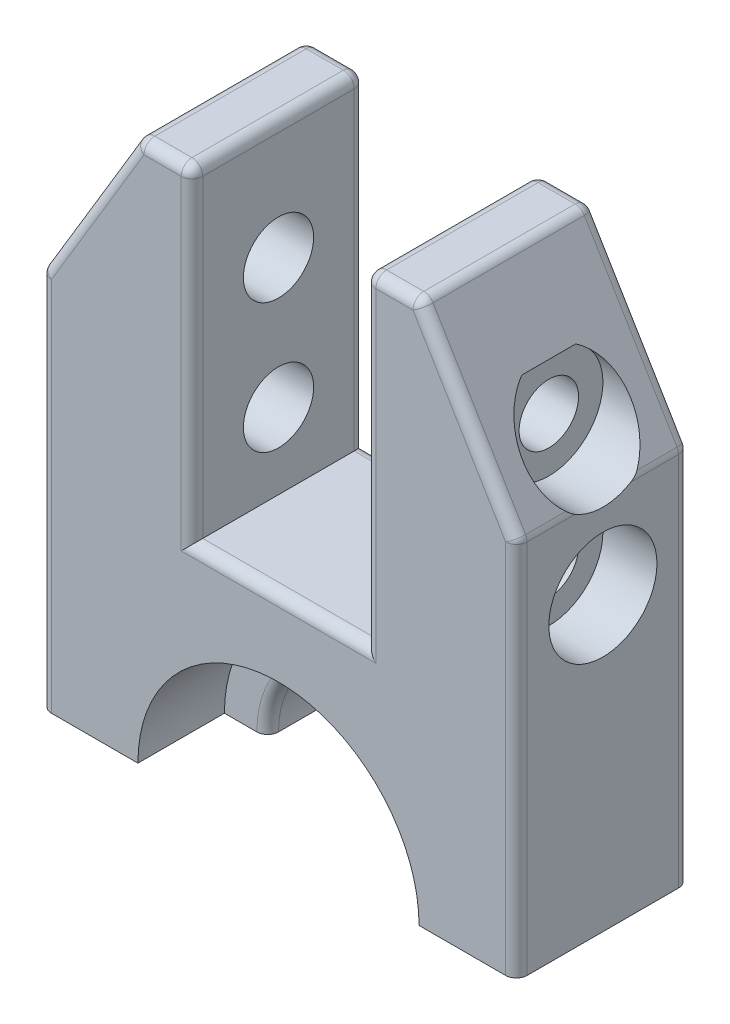
SolidWorks part; units mm, degrees
ref_plane "Płaszczyzna przednia" through (0, 0, 0) normal (0, 0, 1) x (1, 0, 0)
ref_plane "Płaszczyzna górna" through (0, 0, 0) normal (0, 1, 0) x (1, 0, 0)
ref_plane "Płaszczyzna prawa" through (0, 0, 0) normal (1, 0, 0) x (0, 0, -1)
sketch "Szkic1" plane through (0, 0, 0) normal (0, 0, 1) x (1, 0, 0)
  line L0 (0, 0) -> (8, 0)
  line L1 (22, 15) -> (22, -20)
  line L2 (22, -20) -> (0, -20)
  line L3 (0, -20) -> (0, 0)
  line L4 (8, 0) -> (8, 30)
  line L5 (8, 30) -> (13, 30)
  line L6 (13, 30) -> (22, 15)
  dimension "D1" = 8
  dimension "D2" = 20
  dimension "D3" = 22
  dimension "D4" = 15
  dimension "D5" = 5
  dimension "D6" = 35
extrude "Dodanie-wyciągnięcie1" add sketch "Szkic1" along normal mid plane 16
mirror "Lustro1" about plane through (0, -20, 8) normal (1, 0, 0) of "Dodanie-wyciągnięcie1"
sketch "Szkic2" plane through (0, 0, 8) normal (0, 0, 1) x (1, 0, 0)
  line L0 (-22, -20) -> (22, -20) construction
  line L1 (-13, -20) -> (13, -20)
  arc A0 (13, -20) -> (-13, -20) centre (0, -20) ccw
  dimension "D1" = 26
extrude "Wytnij-wyciągnięcie1" cut sketch "Szkic2" against normal blind 8
sketch "Szkic3" plane through (0, 0, 0) normal (0, 0, 1) x (1, 0, 0)
  line L1 (-13, -20) -> (13, -20)
  line L2 (-13, -20) -> (13, -20) construction
  arc A0 (9, -20) -> (-9, -20) centre (0, -20) ccw
  arc A1 (13, -20) -> (-13, -20) centre (0, -20) ccw
  arc A2 (13, -20) -> (-13, -20) centre (0, -20) ccw construction
  dimension "D1" = 0
  dimension "D2" = 4
extrude "Wytnij-wyciągnięcie2" cut sketch "Szkic3" against normal through all and the other way through all contours A0
hole_wizard "Otwory ustalające Ø5.0mm1" positions "Szkic6" profile "Szkic7" hole size "Ø5.0" standard "Ansi Metric"
sketch "Szkic6" plane through (0, -20, 0) normal (0, -1, 0) x (-1, 0, 0)
  point P0 (-17.5, 0)
  point P2 (17.5, 0)
  dimension "D1" = 35
  dimension "D2" = 17.5
sketch "Szkic7" plane through (17.5, -20, 0) normal (1, 0, 0) x (0, 0, -1)
  line L0 (0, 0) -> (0, 21.5022)
  line L1 (0, 21.5022) -> (2.5, 20)
  line L2 (2.5, 20) -> (2.5, 0)
  line L5 (2.5, 0) -> (0, 0)
  line L10 (0, 21.5022) -> (-2.5, 20) construction
  line L11 (0, -6.35) -> (0, 107.95) construction
  dimension "Średnica otworu" = 5
  dimension "Głębokość otworu" = 20
  dimension "Kąt wiertła" = 118
sketch "Szkic8" plane through (0, -20, 0) normal (0, -1, 0) x (-1, 0, 0)
  circle A0 centre (17.5, 0) radius 2.5 construction
  circle A1 centre (-17.5, 0) radius 2.5 construction
  circle A4 centre (-17.5, 0) radius 2.5 construction
  circle A5 centre (17.5, 0) radius 2.5 construction
  circle A6 centre (17.5, 0) radius 3.15
  circle A7 centre (-17.5, 0) radius 3.15
  dimension "D1" = 6.3
extrude "Wytnij-wyciągnięcie3" cut sketch "Szkic8" against normal blind 10
fillet "Zaokrąglenie1" radius 1 26 edges at (8, 30, 0) (22, -2.5, 8) (13, 30, 0) (22, 15, 0) (17.5, 22.5, 8) (10.5, 30, 8) (-8, 15, 8) (-10.5, 30, 8) (-8, 30, 0) (-17.5, 22.5, 8) (-13, 30, 0) (-22, -2.5, 8) (-22, 15, 0) (-22, -2.5, -8) (8, 15, 8) (-17.5, 22.5, -8) (-10.5, 30, -8) (-8, 15, -8) (0, 0, 8) (0, -11, 0) (0, -11, -8) (0, 0, -8) (8, 15, -8) (10.5, 30, -8) (17.5, 22.5, -8) (22, -2.5, -8)
ref_plane "Płaszczyzna1" through (15, 0, 0) normal (1, 0, 0) x (0, 0, -1)
hole_wizard "Pogłębienie walcowe pod M5 Śrubę z łbem walcowym z gniazdem2" positions "Szkic12" profile "Szkic13" counterbore size "M5" standard "Ansi Metric"
sketch "Szkic12" plane through (22, 156, 204.3495) normal (1, 0, 0) x (0, 0, -1)
  line L1 (197.3495, -176) -> (211.3495, -176) construction
  point P0 (204.3495, -149)
  point P2 (204.3495, -137)
sketch "Szkic13" plane through (22, 7, 0) normal (0, 1, 0) x (0, 0, -1)
  line L0 (0, 0) -> (0, 45.6524)
  line L1 (0, 45.6524) -> (2.75, 44)
  line L2 (2.75, 44) -> (2.75, 5)
  line L3 (2.75, 5) -> (5, 5)
  line L4 (5, 5) -> (5, 0)
  line L5 (5, 0) -> (0, 0)
  line L6 (0, 45.6524) -> (-2.75, 44) construction
  line L7 (0, -6.35) -> (0, 107.95) construction
  dimension "Średnica otworu" = 5.5
  dimension "Głębokość otworu" = 44
  dimension "Średnica pogłębienia walcowego" = 10
  dimension "Głębokość pogłębienia walcowego" = 5
  dimension "Kąt wiertła" = 118
sketch "Szkic11" plane through (-8, 0, 0) normal (1, 0, 0) x (0, 0, -1)
  circle A4 centre (0, 7) radius 3.25
  circle A5 centre (0, 19) radius 3.25
  circle A6 centre (0, 7) radius 2.75 construction
  circle A7 centre (0, 19) radius 2.75 construction
  dimension "D1" = 6.5
extrude "Wytnij-wyciągnięcie4" cut sketch "Szkic11" against normal through all
equation "\"D2@Szkic6\"=\"D1@Szkic6\"/2"
